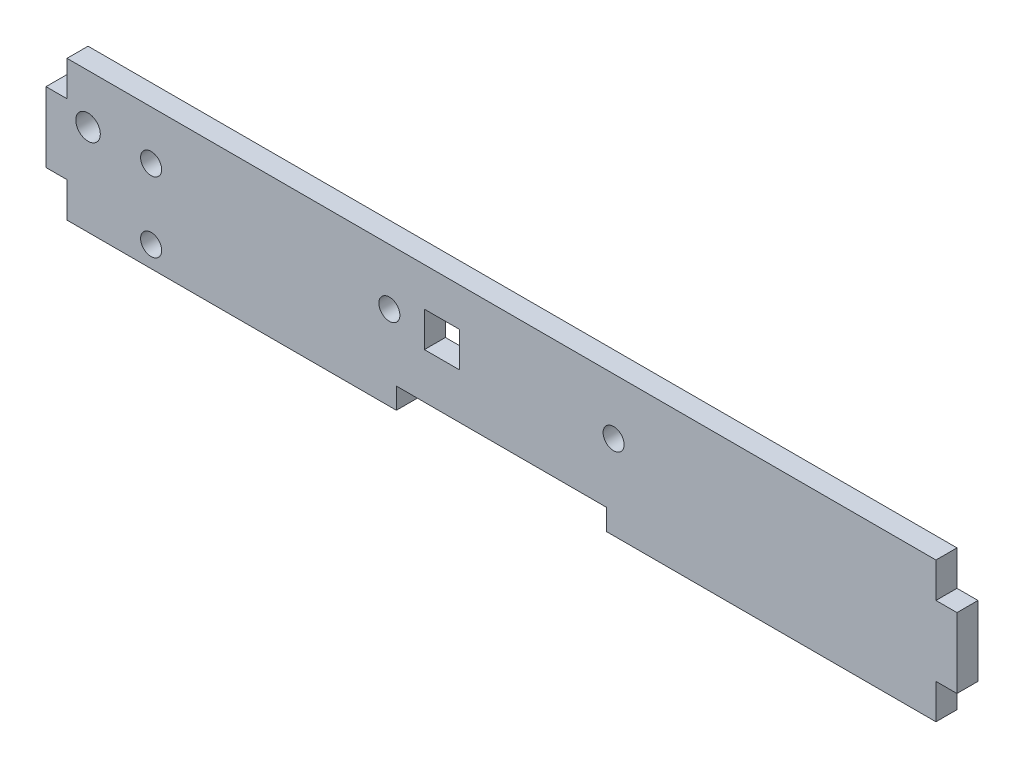
SolidWorks part; units mm, degrees
ref_plane "Front Plane" through (0, 0, 0) normal (0, 0, 1) x (1, 0, 0)
ref_plane "Top Plane" through (0, 0, 0) normal (0, 1, 0) x (1, 0, 0)
ref_plane "Right Plane" through (0, 0, 0) normal (1, 0, 0) x (0, 0, -1)
sketch "Sketch1" plane through (0, 0, 0) normal (0, 0, 1) x (1, 0, 0)
  line L0 (0, 0) -> (3, 0)
  line L1 (3, 0) -> (3, -5)
  line L2 (3, -5) -> (50, -5)
  line L3 (50, -5) -> (50, -2)
  line L4 (50, -2) -> (80, -2)
  line L5 (80, -2) -> (80, -5)
  line L6 (80, -5) -> (127, -5)
  line L7 (127, -5) -> (127, 0)
  line L8 (127, 0) -> (130, 0)
  line L9 (130, 0) -> (130, 10)
  line L10 (130, 10) -> (127, 10)
  line L11 (127, 10) -> (127, 15)
  line L12 (127, 15) -> (3, 15)
  line L13 (3, 15) -> (3, 10)
  line L14 (3, 10) -> (0, 10)
  line L15 (0, 10) -> (0, 0)
  dimension "D1" = 10
  dimension "D2" = 5
  dimension "D3" = 30
  dimension "D4" = 3
  dimension "D5" = 124
extrude "Boss-Extrude1" add sketch "Sketch1" along normal blind 3
sketch "Sketch2" plane through (0, 0, 3) normal (0, 0, 1) x (1, 0, 0)
  line L0 (3, -5) -> (50, -5) construction
  line L1 (3, 0) -> (3, -5) construction
  line L2 (127, 15) -> (3, 15) construction
  circle A0 centre (15, 8) radius 1.5
  circle A1 centre (15, -2) radius 1.5
  circle A2 centre (6, 8) radius 1.75
  dimension "D1" = 3
  dimension "D2" = 10
  dimension "D3" = 3
  dimension "D4" = 12
  dimension "D5" = 9
  dimension "D6" = 3.5
  dimension "D7" = 7
extrude "Cut-Extrude1" cut sketch "Sketch2" against normal through all
sketch "Sketch3" plane through (0, 0, 3) normal (0, 0, 1) x (1, 0, 0)
  line L0 (127, 15) -> (3, 15) construction
  line L1 (54, 9.5) -> (59, 9.5)
  line L2 (54, 9.5) -> (54, 4.5)
  line L3 (54, 4.5) -> (59, 4.5)
  line L4 (59, 9.5) -> (59, 4.5)
  line L5 (127, 10) -> (127, 15) construction
  circle A0 centre (49, 7) radius 1.5
  circle A1 centre (81, 7) radius 1.5
  dimension "D1" = 3
  dimension "D7" = 8
  dimension "D8" = 46
  dimension "D2" = 5
  dimension "D3" = 5
  dimension "D4" = 5
  dimension "D5" = 2.5
  dimension "D6" = 32
extrude "Cut-Extrude2" cut sketch "Sketch3" against normal through all
